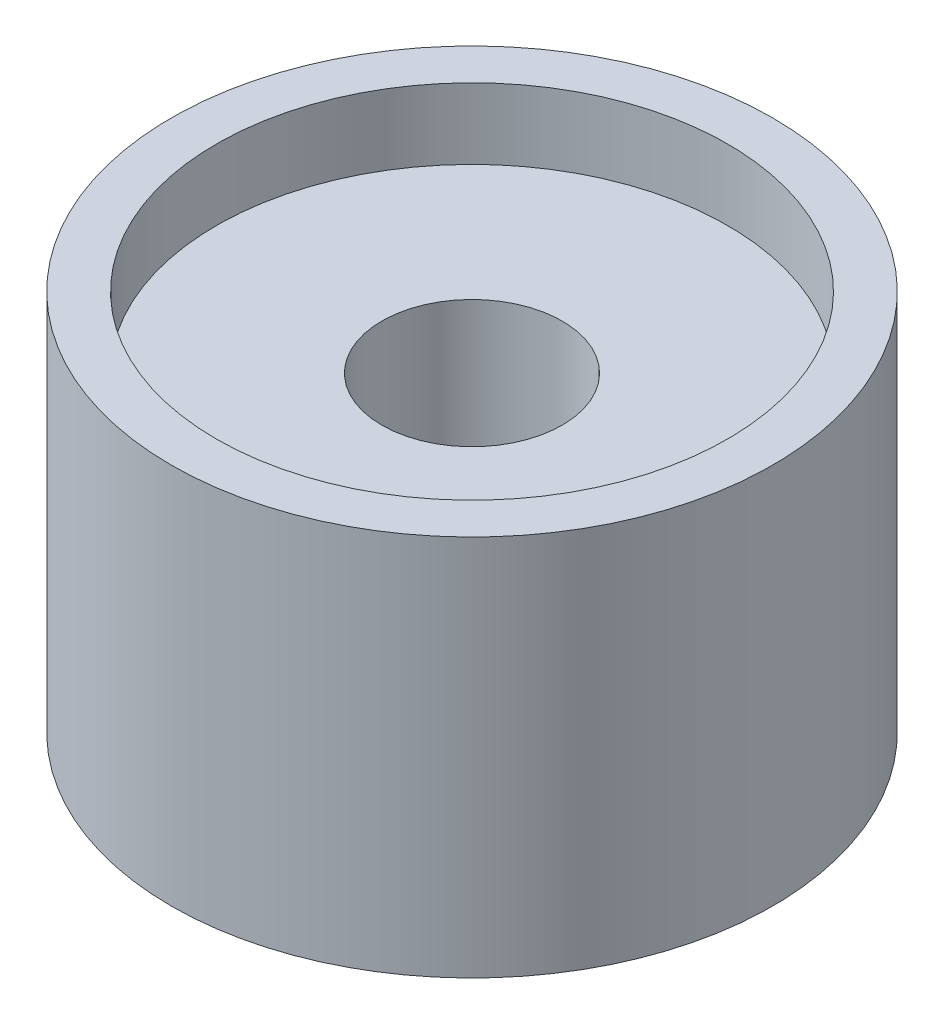
SolidWorks part; units mm, degrees
ref_plane "Front" through (0, 0, 0) normal (0, 0, 1) x (1, 0, 0)
ref_plane "Top" through (0, 0, 0) normal (0, 1, 0) x (1, 0, 0)
ref_plane "Right" through (0, 0, 0) normal (1, 0, 0) x (0, 0, -1)
sketch "Sketch1" plane through (0, 0, 0) normal (0, 1, 0) x (1, 0, 0)
  circle A0 centre (0, 0) radius 100
  circle A1 centre (0, 0) radius 85
  dimension "D1" = 170
  dimension "D2" = 200
extrude "Boss-Extrude1" add sketch "Sketch1" along normal mid plane 127
sketch "Sketch4" plane through (0, 0, 0) normal (0, 1, 0) x (1, 0, 0)
  circle A0 centre (0, 0) radius 85
  circle A1 centre (0, 0) radius 30
  dimension "D1" = 170
extrude "Boss-Extrude2" add sketch "Sketch4" along normal mid plane 80
